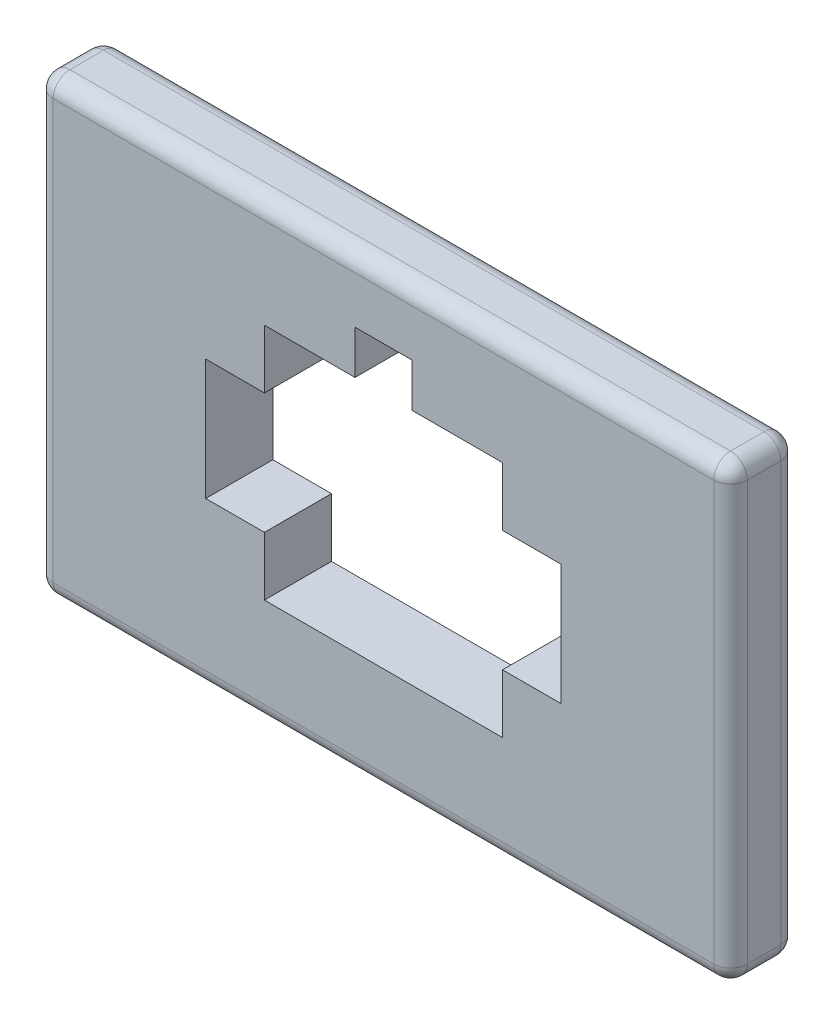
SolidWorks part; units mm, degrees
ref_plane "Front Plane" through (0, 0, 0) normal (0, 0, 1) x (1, 0, 0)
ref_plane "Top Plane" through (0, 0, 0) normal (0, 1, 0) x (1, 0, 0)
ref_plane "Right Plane" through (0, 0, 0) normal (1, 0, 0) x (0, 0, -1)
sketch "Sketch1" plane through (0, 0, 0) normal (0, 0, 1) x (1, 0, 0)
  line L1 (-10.35, -6.75) -> (10.35, -6.75)
  line L2 (-10.35, -6.75) -> (-10.35, 6.75)
  line L3 (-10.35, 6.75) -> (10.35, 6.75)
  line L4 (10.35, -6.75) -> (10.35, 6.75)
  line L5 (-10.35, -6.75) -> (10.35, 6.75) construction
  line L6 (-10.35, 6.75) -> (10.35, -6.75) construction
  point P0 (0, 0)
  dimension "D1" = 20.7
  dimension "D2" = 13.5
extrude "Boss-Extrude1" add sketch "Sketch1" along normal blind 2
fillet "Fillet1" radius 0.5 12 edges at (0, -6.75, 2) (0, -6.75, 0) (-10.35, 0, 2) (-10.35, -6.75, 1) (-10.35, 0, 0) (0, 6.75, 2) (-10.35, 6.75, 1) (0, 6.75, 0) (10.35, -6.75, 1) (10.35, 0, 2) (10.35, 6.75, 1) (10.35, 0, 0)
sketch "Sketch2" plane through (0, 0, 2) normal (0, 0, 1) x (1, 0, 0)
  line L22 (5.3, -1.8) -> (-5.3, -1.8)
  line L23 (5.3, -1.8) -> (5.3, 1.8)
  line L28 (5.3, 1.8) -> (-5.3, 1.8)
  line L29 (-5.3, -1.8) -> (-5.3, 1.8)
  line L34 (5.3, -1.8) -> (-5.3, 1.8) construction
  line L35 (5.3, 1.8) -> (-5.3, -1.8) construction
  line L36 (3.55, -3.55) -> (-3.55, -3.55)
  line L37 (3.55, -3.55) -> (3.55, 3.55)
  line L38 (3.55, 3.55) -> (-3.55, 3.55)
  line L39 (-3.55, -3.55) -> (-3.55, 3.55)
  line L40 (3.55, -3.55) -> (-3.55, 3.55) construction
  line L41 (3.55, 3.55) -> (-3.55, -3.55) construction
  line L42 (-0.85, 4.85) -> (0.85, 4.85)
  line L43 (-0.85, 4.85) -> (-0.85, 0)
  line L44 (-0.85, 0) -> (0.85, 0)
  line L45 (0.85, 4.85) -> (0.85, 0)
  point P0 (0, 0)
  point P2 (0, 0)
  point P9 (0, 0)
  point P24 (9.1173, -1.0121)
  point P26 (-20.9327, 10.8379)
  point P29 (0, 0)
  point P31 (2.5339, 6.177)
  point P32 (0.2673, -2.7621)
  dimension "D1" = 3.6
  dimension "D2" = 7.1
  dimension "D3" = 1.7
  dimension "D4" = 1.3
  dimension "D5" = 1.75
  dimension "D6" = 7.1
extrude "Cut-Extrude1" cut sketch "Sketch2" against normal through all contours L38 L39 L36 L37 | L45 L44 L43 L42 | L28 L29 L22 L23
